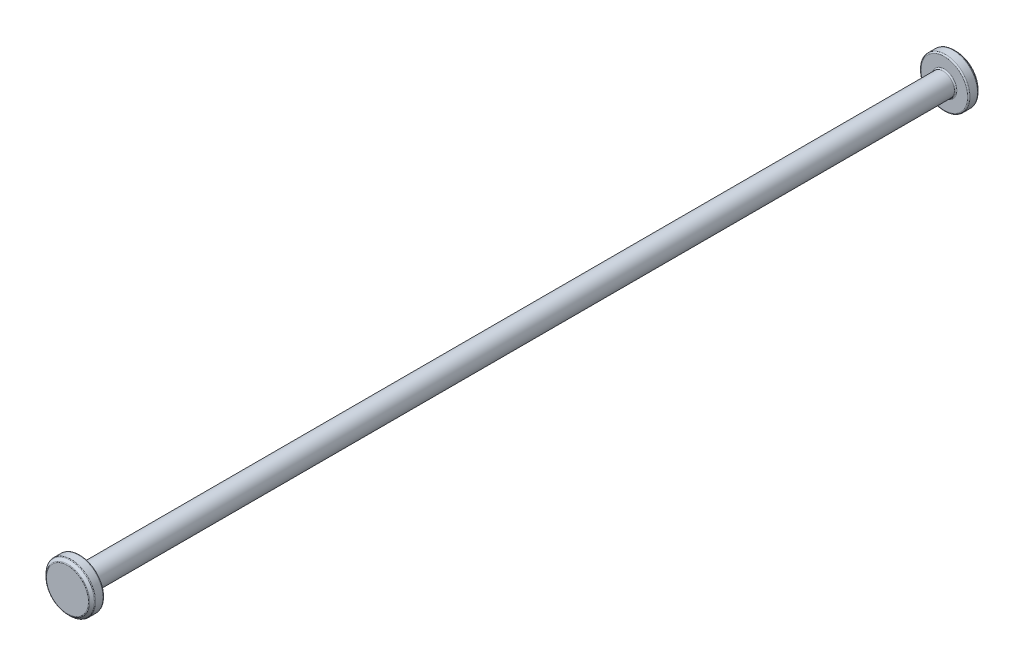
SolidWorks part; units mm, degrees
ref_plane "Front Plane" through (0, 0, 0) normal (0, 0, 1) x (1, 0, 0)
ref_plane "Top Plane" through (0, 0, 0) normal (0, 1, 0) x (1, 0, 0)
ref_plane "Right Plane" through (0, 0, 0) normal (1, 0, 0) x (0, 0, -1)
sketch "Sketch1" plane through (0, 0, 0) normal (0, 0, 1) x (1, 0, 0)
  circle A0 centre (0, 0) radius 0.925
  dimension "D1" = 1.85
extrude "Boss-Extrude1" add sketch "Sketch1" along normal blind 35.25
sketch "Sketch2" plane through (0, 0, 35.25) normal (0, 0, 1) x (1, 0, 0)
  circle A0 centre (0, 0) radius 2
  dimension "D1" = 4
extrude "Boss-Extrude2" add sketch "Sketch2" along normal blind 1
chamfer "Chamfer1" distance 0.25 angle 45 1 edges at (2, 0, 36.25)
mirror "Mirror1" about plane through (0, 0, 0) normal (0, 0, 1) of bodies 102
fillet "Fillet1" radius 0.1 8 edges at (2, 0, -35.25) (0.925, 0, -35.25) (1.75, 0, -36.25) (2, 0, -36) (2, 0, 35.25) (0.925, 0, 35.25) (2, 0, 36) (1.75, 0, 36.25)
